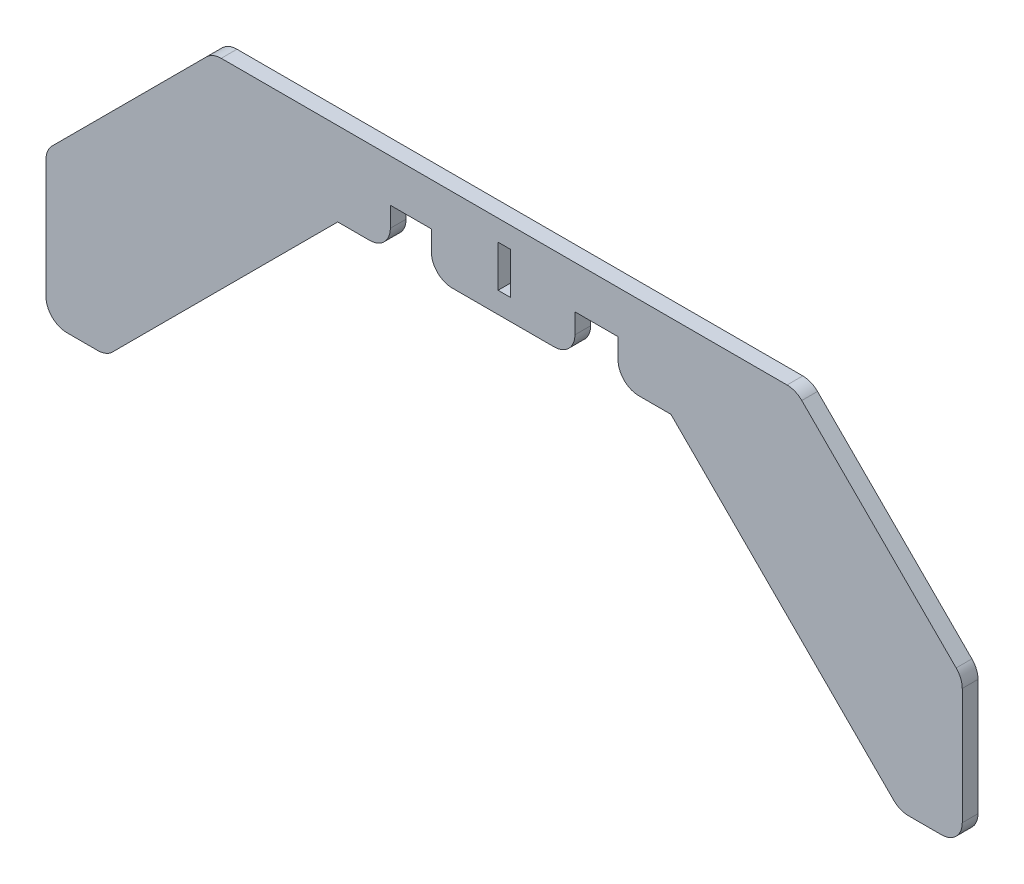
SolidWorks part; units mm, degrees
ref_plane "Front Plane" through (0, 0, 0) normal (0, 0, 1) x (1, 0, 0)
ref_plane "Top Plane" through (0, 0, 0) normal (0, 1, 0) x (1, 0, 0)
ref_plane "Right Plane" through (0, 0, 0) normal (1, 0, 0) x (0, 0, -1)
other "Center of Mass"
sketch "Sketch1" plane through (0, 0, 0) normal (0, 0, 1) x (1, 0, 0)
  line L1 (0, 0) -> (279.4, 0)
  line L2 (0, 0) -> (0, 254)
  line L3 (0, 254) -> (279.4, 254)
  line L4 (279.4, 0) -> (279.4, 254)
  line L5 (0, 0) -> (279.4, 254) construction
  line L6 (0, 254) -> (279.4, 0) construction
  point P4 (139.7, 127)
  dimension "D1" = 279.4
  dimension "D2" = 254
extrude "Boss-Extrude1" add sketch "Sketch1" along normal blind 4.8
ref_plane "Plane1" through (139.7, 0, 0) normal (-1, 0, 0) x (0, 0, 1)
sketch "Sketch4" plane through (0, 0, 0) normal (0, 0, -1) x (-1, 0, 0)
  line L17 (-88.9, 168.7277) -> (-190.5, 168.7277)
  line L20 (-18.4112, 72.7241) -> (-88.9574, 143.2703)
  line L22 (-88.9574, 143.2703) -> (-190.5574, 143.2703)
  line L23 (-279.4, 73.4777) -> (-260.35, 73.4777)
  line L24 (-190.5574, 143.2703) -> (-260.35, 73.4777)
  line L25 (-88.9, 168.7277) -> (-50.8, 168.7277)
  line L28 (-279.4, 117.9277) -> (-279.4, 73.4777)
  line L29 (-88.9, 156.0277) -> (-190.5, 156.0277) construction
  line L30 (-141.6624, 162.3777) -> (-137.8524, 162.3777)
  line L35 (-141.6624, 162.3777) -> (-141.6624, 149.6777)
  line L36 (-141.6624, 149.6777) -> (-137.8524, 149.6777)
  line L37 (-137.8524, 162.3777) -> (-137.8524, 149.6777)
  line L38 (-105.0011, 143.2703) -> (-117.5137, 143.2703)
  line L39 (-105.0011, 143.2703) -> (-105.0011, 155.7128)
  line L40 (-105.0011, 155.7128) -> (-117.5137, 155.7128)
  line L41 (-117.5137, 143.2703) -> (-117.5137, 155.7128)
  line L42 (-105.0011, 143.2703) -> (-117.5137, 155.7128) construction
  line L43 (-105.0011, 155.7128) -> (-117.5137, 143.2703) construction
  line L44 (-161.2832, 143.2703) -> (-174.4316, 143.2703)
  line L45 (-161.2832, 143.2703) -> (-161.2832, 155.7128)
  line L46 (-161.2832, 155.7128) -> (-174.4316, 155.7128)
  line L47 (-174.4316, 143.2703) -> (-174.4316, 155.7128)
  line L48 (-161.2832, 143.2703) -> (-174.4316, 155.7128) construction
  line L49 (-161.2832, 155.7128) -> (-174.4316, 143.2703) construction
  line L50 (-141.6624, 162.3777) -> (-137.8524, 149.6777) construction
  line L51 (-141.6624, 149.6777) -> (-137.8524, 162.3777) construction
  line L52 (-190.5, 168.7277) -> (-228.6, 168.7277)
  line L53 (-18.4112, 72.7241) -> (0, 72.7241)
  line L54 (-50.8, 168.7277) -> (0, 117.9277)
  line L55 (-228.6, 168.7277) -> (-279.4, 117.9277)
  line L56 (0, 254) -> (0, 0) construction
  line L57 (0, 72.7241) -> (0, 117.9277)
  point P14 (-139.7574, 156.0277)
  point P16 (-139.7574, 149.6777)
  point P22 (-111.2574, 149.4915)
  point P27 (-167.8574, 149.4915)
  point P32 (-167.8574, 149.6203)
  point P33 (-111.2574, 149.6203)
  dimension "D1" = 3.81
  dimension "D3" = 50.8
  dimension "D4" = 0
  dimension "D5" = 0
  dimension "D6" = 0
  dimension "D7" = 6.35
  dimension "D8" = 38.1
extrude "Cut-Extrude1" cut sketch "Sketch4" against normal through all
fillet "Fillet1" radius 6.35 12 edges at (18.4112, 72.7241, 2.4) (0, 72.7241, 2.4) (279.4, 73.4777, 2.4) (260.35, 73.4777, 2.4) (174.4316, 143.2703, 2.4) (161.2832, 143.2703, 2.4) (117.5137, 143.2703, 2.4) (105.0011, 143.2703, 2.4) (228.6, 168.7277, 2.4) (279.4, 117.9277, 2.4) (0, 117.9277, 2.4) (50.8, 168.7277, 2.4)
equation "\"MDF\"= 4.8mm"
equation "\"Foamcore\"= 4.6mm"
equation "\"PCB\" = 1.6mm"
equation "\"GMaterial\"= \"MDF\""
equation "\"BaseWidth\" = 10in"
equation "\"SkidLength\" = 1in"
equation "\"SkidClearance\" = 0.4in"
equation "\"MotorMountLength\" = 2in"
equation "\"MotorMountWidth\" = \"GMaterial\""
equation "\"MotorMountHeight\" = 2.25in"
equation "\"UnoStackWidth\" = 77.4mm"
equation "\"UnoStackLength\" = 79.8mm"
equation "\"UnoStackHeight\" = 34.2mm"
equation "\"TallHexRiserHeight\" = 22.2mm"
equation "\"PingPongBallSize\" = 40mm"
equation "\"BarrelLength\" = 9in"
equation "\"BarrelSize\" = \"PingPongBallSize\""
equation "\"PlatformLength\" = 4in"
equation "\"PlatformWidth\" = 6in"
equation "\"WheelWidth\"= 26mm"
equation "\"WheelDiameter\"=2.99213"
equation "\"ServoMountHeight\"=2.49223"
equation "\"ServoGearHeight\" = 0.95330261in"
equation "\"ServoMountLength\"= 1.53774"
equation "\"PivotHoleRadius\"= 0.616358"
equation "\"PlatformMountHeight\" = 3.19"
equation "\"TensionOffSet\"= .3mm"
equation "\"MotorMountWedge\"=0.333333"
equation "\"LaserCutterOffset\"= .3mm"
equation "\"D1@Boss-Extrude1\"=\"GMaterial\""
equation "\"BumperWidth\"=11"
equation "\"D1@Sketch1\"=\"BumperWidth\""
equation "\"D2@Sketch1\"=\"BaseWidth\""
